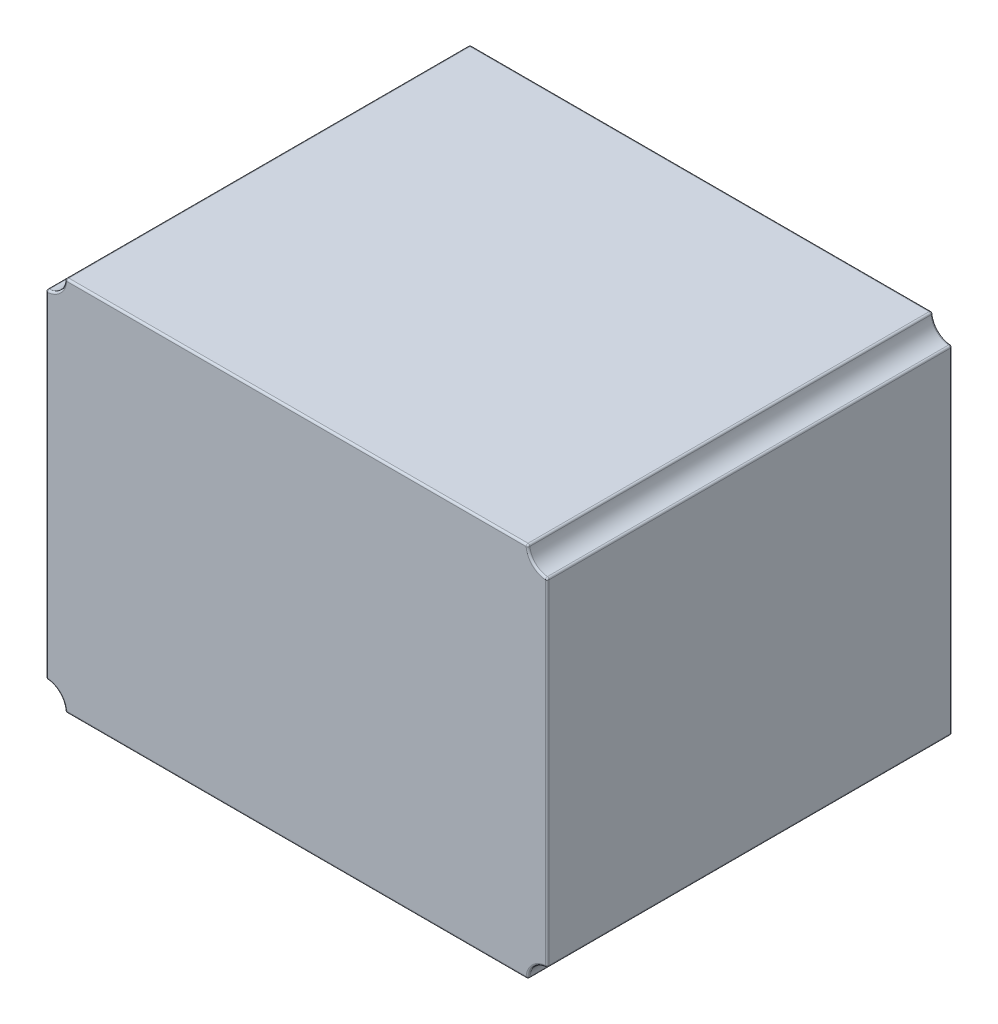
SolidWorks part; units mm, degrees
ref_plane "Front Plane" through (0, 0, 0) normal (0, 0, 1) x (1, 0, 0)
ref_plane "Top Plane" through (0, 0, 0) normal (0, 1, 0) x (1, 0, 0)
ref_plane "Right Plane" through (0, 0, 0) normal (1, 0, 0) x (0, 0, -1)
sketch "Sketch1" plane through (0, 0, 0) normal (0, 0, 1) x (1, 0, 0)
  line L1 (0, 0) -> (260, 0)
  line L2 (0, 0) -> (0, -195)
  line L3 (0, -195) -> (260, -195)
  line L4 (260, 0) -> (260, -195)
  dimension "D1" = 260
  dimension "D2" = 195
extrude "Boss-Extrude1" add sketch "Sketch1" against normal blind 210
sketch "Sketch2" plane through (0, 0, 0) normal (0, 0, 1) x (1, 0, 0)
  circle A0 centre (0, 0) radius 10
  circle A1 centre (260, 0) radius 10
  circle A2 centre (0, -195) radius 10
  circle A3 centre (260, -195) radius 10
  dimension "D1" = 20
  dimension "D2" = 20
  dimension "D3" = 20
  dimension "D4" = 20
extrude "Cut-Extrude1" cut sketch "Sketch2" against normal blind 210
fillet "Fillet1" radius 1 24 edges at (7.0711, -7.0711, 0) (130, 0, -210) (260, -97.5, -210) (130, -195, -210) (0, -97.5, -210) (130, 0, 0) (260, -97.5, 0) (130, -195, 0) (0, -97.5, 0) (250, 0, -105) (260, -10, -105) (0, -185, -105) (10, -195, -105) (260, -185, -105) (250, -195, -105) (0, -10, -105) (10, 0, -105) (7.0711, -7.0711, -210) (252.9289, -7.0711, -210) (252.9289, -7.0711, 0) (7.0711, -187.9289, -210) (7.0711, -187.9289, 0) (252.9289, -187.9289, -210) (252.9289, -187.9289, 0)
sketch "Sketch4" plane through (0, 0, 0) normal (-1, 0, 0) x (0, 0, 1)
  text T0 "\r\n\r\nEZZAYRA\r\nKICHKICH" font "Century Gothic" height in points 72
extrude "Cut-Extrude2" cut sketch "Sketch4" against normal blind 60
